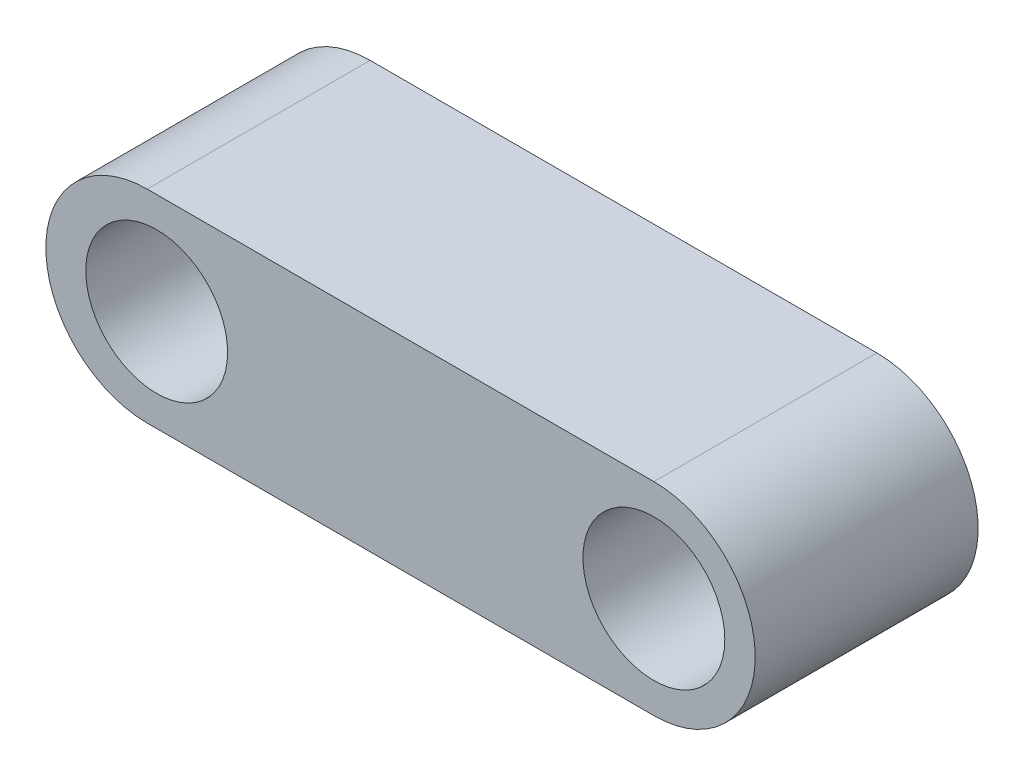
SolidWorks part; units mm, degrees
ref_plane "Front Plane" through (0, 0, 0) normal (0, 0, 1) x (1, 0, 0)
ref_plane "Top Plane" through (0, 0, 0) normal (0, 1, 0) x (1, 0, 0)
ref_plane "Right Plane" through (0, 0, 0) normal (1, 0, 0) x (0, 0, -1)
sketch "Sketch1" plane through (0, 0, 0) normal (0, 0, 1) x (1, 0, 0)
  line L1 (0, 0) -> (25, 0)
  line L2 (0, 0) -> (0, -10)
  line L3 (0, -10) -> (25, -10)
  line L4 (25, 0) -> (25, -10)
  circle A0 centre (25, -5) radius 5
  circle A1 centre (0, -5) radius 5
  dimension "D2" = 10
  dimension "D1" = 25
extrude "Boss-Extrude1" add sketch "Sketch1" along normal blind 11 contours A0 | L2 L1 L4 L3 | A1
sketch "Sketch2" plane through (0, 0, 11) normal (0, 0, 1) x (1, 0, 0)
  line L0 (25, -5) -> (0.4693, -5) construction
  circle A0 centre (0.4693, -5) radius 3.5
  circle A1 centre (25, -5) radius 3.5
  point P6 (0, 0)
  dimension "D1" = 7
extrude "Cut-Extrude1" cut sketch "Sketch2" against normal up to surface (11 mm away) up to face at (12.5, -5, 0)
